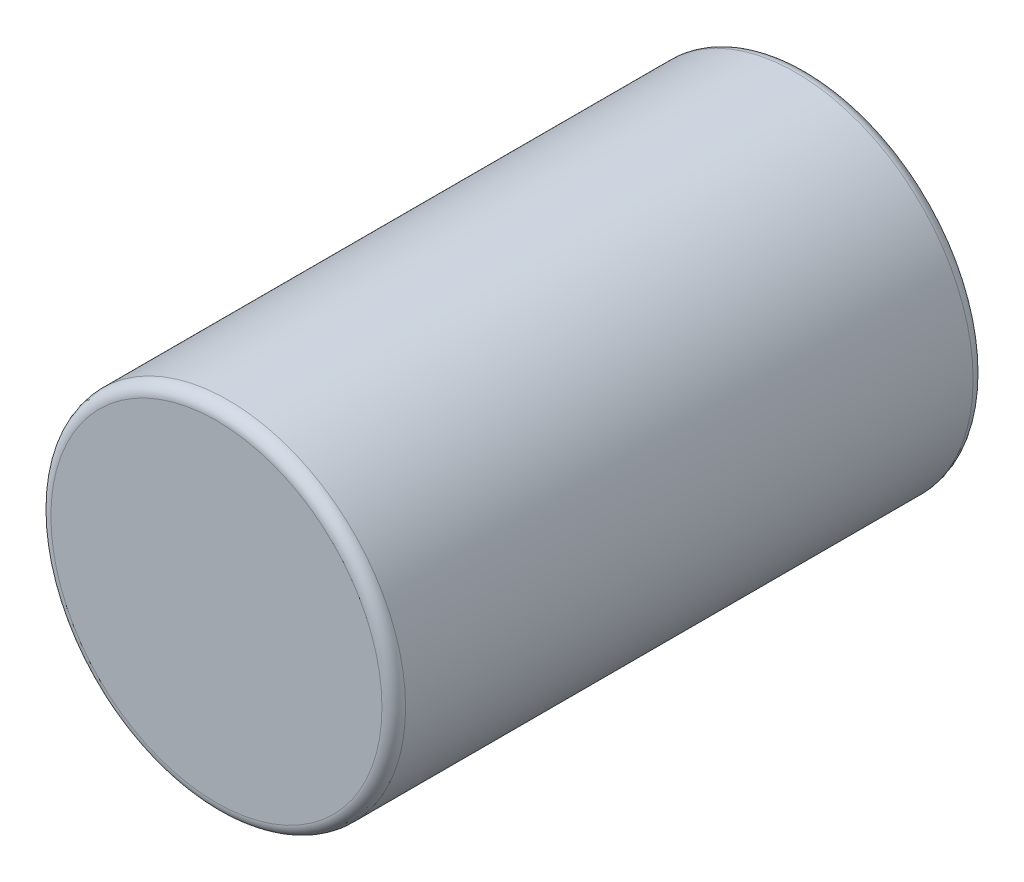
SolidWorks part; units mm, degrees
ref_plane "정면" through (0, 0, 0) normal (0, 0, 1) x (1, 0, 0)
ref_plane "윗면" through (0, 0, 0) normal (0, 1, 0) x (1, 0, 0)
ref_plane "우측면" through (0, 0, 0) normal (1, 0, 0) x (0, 0, -1)
sketch "스케치1" plane through (0, 0, 0) normal (0, 0, 1) x (1, 0, 0)
  circle A0 centre (0, 0) radius 3
  dimension "D1" = 6
extrude "보스-돌출1" add sketch "스케치1" along normal blind 10
fillet "필렛1" radius 0.2 2 edges at (3, 0, 0) (3, 0, 10)
